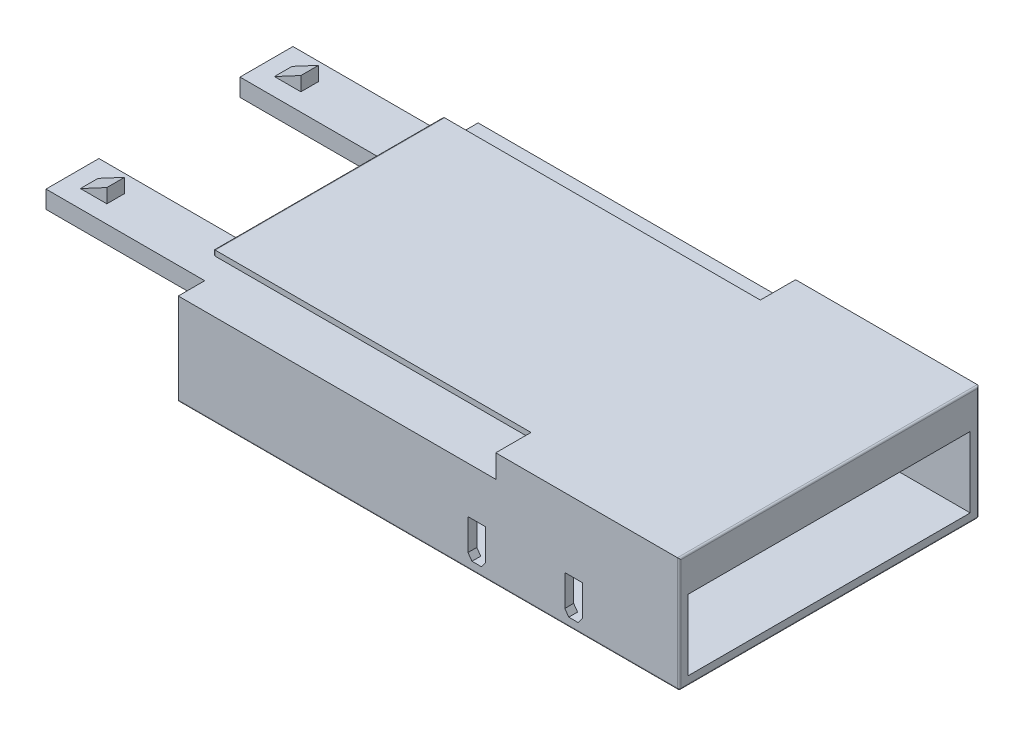
SolidWorks part; units mm, degrees
ref_plane "Front Plane" through (0, 0, 0) normal (0, 0, 1) x (1, 0, 0)
ref_plane "Top Plane" through (0, 0, 0) normal (0, 1, 0) x (1, 0, 0)
ref_plane "Right Plane" through (0, 0, 0) normal (1, 0, 0) x (0, 0, -1)
sketch "Sketch1" plane through (0, 0, 0) normal (0, 1, 0) x (1, 0, 0)
  line L1 (0, 0) -> (284, 0)
  line L2 (0, 0) -> (0, 170)
  line L3 (0, 170) -> (284, 170)
  line L4 (284, 0) -> (284, 170)
  dimension "D1" = 170
  dimension "D2" = 284
extrude "Boss-Extrude1" add sketch "Sketch1" along normal blind 65
sketch "Sketch2" plane through (0, 0, 0) normal (-1, 0, 0) x (0, 0, 1)
  line L0 (-170, 65) -> (-170, 0) construction
  line L1 (-150, 65) -> (-20, 65) construction
  line L2 (-150, 65) -> (-150, 62) construction
  line L3 (-150, 62) -> (-140, 62) construction
  line L4 (-20, 65) -> (-20, 62) construction
  line L6 (-140, 62) -> (-140, 52) construction
  line L7 (-140, 52) -> (-30, 52) construction
  line L8 (-30, 62) -> (-30, 52) construction
  line L9 (-170, 65) -> (0, 65) construction
  line L10 (-30, 62) -> (-20, 62) construction
  line L11 (-140, 52) -> (-170, 52)
  line L12 (-170, 52) -> (-170, 65)
  line L13 (-170, 65) -> (-150, 65)
  line L14 (-150, 65) -> (-150, 62)
  line L15 (-150, 62) -> (-140, 62)
  line L16 (-140, 62) -> (-140, 52)
  line L17 (-30, 52) -> (0, 52)
  line L18 (0, 65) -> (0, 0) construction
  line L19 (0, 52) -> (0, 65)
  line L20 (0, 65) -> (-20, 65)
  line L21 (-20, 65) -> (-20, 62)
  line L22 (-20, 62) -> (-30, 62)
  line L23 (-30, 62) -> (-30, 52)
  dimension "D1" = 130
  dimension "D2" = 3
  dimension "D3" = 10
  dimension "D4" = 110
  dimension "D5" = 20
  dimension "D6" = 10
extrude "Cut-Extrude1" cut sketch "Sketch2" against normal blind 180
sketch "Sketch3" plane through (0, 0, 0) normal (-1, 0, 0) x (0, 0, 1)
  line L0 (-170, 52) -> (-170, 0) construction
  line L1 (-155, 52) -> (-125, 52)
  line L2 (-155, 52) -> (-155, 42)
  line L3 (-155, 42) -> (-125, 42)
  line L4 (-125, 52) -> (-125, 42)
  line L5 (-15, 52) -> (-45, 52)
  line L6 (-15, 52) -> (-15, 42)
  line L7 (-15, 42) -> (-45, 42)
  line L8 (-45, 52) -> (-45, 42)
  line L9 (-170, 52) -> (-140, 52) construction
  line L10 (-30, 52) -> (0, 52) construction
  dimension "D1" = 30
  dimension "D2" = 30
  dimension "D3" = 10
  dimension "D4" = 10
  dimension "D5" = 80
  dimension "D6" = 15
extrude "Boss-Extrude2" add sketch "Sketch3" along normal blind 90
sketch "Sketch4" plane through (0, 52, 0) normal (0, 1, 0) x (1, 0, 0)
  line L0 (0, 125) -> (0, 155) construction
  line L1 (0, 155) -> (-90, 155) construction
  line L2 (0, 30) -> (0, 0) construction
  line L4 (-65.5, 145) -> (-80.5, 145)
  line L5 (-65.5, 145) -> (-65.5, 135)
  line L6 (-65.5, 135) -> (-80.5, 135)
  line L7 (-80.5, 145) -> (-80.5, 135)
  line L8 (0, 15) -> (-90, 15) construction
  line L9 (-65.5, 35) -> (-80.5, 35)
  line L10 (-65.5, 35) -> (-65.5, 25)
  line L11 (-65.5, 25) -> (-80.5, 25)
  line L12 (-80.5, 35) -> (-80.5, 25)
  dimension "D1" = 10
  dimension "D2" = 15
  dimension "D3" = 10
  dimension "D4" = 65.5
  dimension "D5" = 10
  dimension "D6" = 15
  dimension "D7" = 65.5
  dimension "D8" = 10
extrude "Boss-Extrude3" add sketch "Sketch4" along normal blind 8
sketch "Sketch5" plane through (0, 0, -25) normal (0, 0, 1) x (1, 0, 0)
  line L0 (-65.5, 60) -> (-80.5, 52)
  line L1 (-65.5, 60) -> (-80.5, 60)
  line L2 (-80.5, 60) -> (-80.5, 52)
sketch "Sketch6" plane through (0, 0, -145) normal (0, 0, -1) x (-1, 0, 0)
  line L0 (65.5, 60) -> (80.5, 52)
  line L1 (65.5, 60) -> (80.5, 60)
  line L2 (80.5, 60) -> (80.5, 52)
extrude "Cut-Extrude2" cut sketch "Sketch6" against normal blind 10
extrude "Cut-Extrude3" cut sketch "Sketch5" against normal blind 10
sketch "Sketch7" plane through (0, 0, 0) normal (0, -1, 0) x (1, 0, 0)
  line L0 (0, -170) -> (0, 0) construction
  line L3 (11, -37.5) -> (11, -132.5) construction
  line L4 (13.5, -37.5) -> (13.5, -132.5)
  line L5 (8.5, -37.5) -> (8.5, -132.5)
  line L6 (56, -37.5) -> (56, -132.5) construction
  line L7 (58.5, -37.5) -> (58.5, -132.5)
  line L8 (53.5, -37.5) -> (53.5, -132.5)
  line L9 (26, -37.5) -> (26, -132.5) construction
  line L10 (28.5, -37.5) -> (28.5, -132.5)
  line L11 (23.5, -37.5) -> (23.5, -132.5)
  line L12 (41, -37.5) -> (41, -132.5) construction
  line L13 (43.5, -37.5) -> (43.5, -132.5)
  line L14 (38.5, -37.5) -> (38.5, -132.5)
  line L15 (0, -85) -> (284, -85) construction
  line L16 (284, 0) -> (284, -170) construction
  arc A2 (13.5, -37.5) -> (8.5, -37.5) centre (11, -37.5) ccw
  arc A3 (8.5, -132.5) -> (13.5, -132.5) centre (11, -132.5) ccw
  arc A4 (58.5, -37.5) -> (53.5, -37.5) centre (56, -37.5) ccw
  arc A5 (53.5, -132.5) -> (58.5, -132.5) centre (56, -132.5) ccw
  arc A6 (28.5, -37.5) -> (23.5, -37.5) centre (26, -37.5) ccw
  arc A7 (23.5, -132.5) -> (28.5, -132.5) centre (26, -132.5) ccw
  arc A8 (43.5, -37.5) -> (38.5, -37.5) centre (41, -37.5) ccw
  arc A9 (38.5, -132.5) -> (43.5, -132.5) centre (41, -132.5) ccw
  point P9 (11, -85)
  point P16 (56, -85)
  point P23 (26, -85)
  point P30 (41, -85)
  point P35 (11, -35)
  point P36 (11, -135)
  point P42 (26, -35)
  point P43 (26, -135)
  point P44 (41, -35)
  point P45 (41, -135)
  point P46 (56, -35)
  point P47 (56, -135)
  dimension "D1" = 8.5
  dimension "D6" = 100
  dimension "D7" = 100
  dimension "D9" = 100
  dimension "D2" = 5
  dimension "D3" = 5
  dimension "D4" = 5
  dimension "D5" = 5
  dimension "D8" = 100
  dimension "D10" = 15
  dimension "D11" = 15
  dimension "D12" = 15
extrude "Cut-Extrude4" cut sketch "Sketch7" against normal blind 5
sketch "Sketch8" plane through (284, 0, 0) normal (1, 0, 0) x (0, 0, -1)
  line L0 (0, 65) -> (0, 0) construction
  line L1 (5, 45) -> (165, 45)
  line L2 (5, 45) -> (5, 5)
  line L3 (5, 5) -> (165, 5)
  line L4 (165, 45) -> (165, 5)
  line L5 (170, 65) -> (170, 0) construction
  line L6 (0, 0) -> (170, 0) construction
  line L7 (0, 65) -> (170, 65) construction
  dimension "D1" = 5
  dimension "D2" = 5
  dimension "D3" = 5
  dimension "D4" = 20
extrude "Cut-Extrude5" cut sketch "Sketch8" against normal blind 279
sketch "Sketch9" plane through (0, 0, 0) normal (0, 0, 1) x (1, 0, 0)
  line L0 (219.15, 25.8) -> (229.05, 25.8)
  line L1 (164.25, 25.8) -> (174.15, 25.8)
  line L2 (164.25, 25.8) -> (164.25, 8.15)
  line L3 (166.5, 5) -> (171.9, 5)
  line L4 (174.15, 25.8) -> (174.15, 8.15)
  line L5 (219.15, 25.8) -> (219.15, 8.15)
  line L6 (221.4, 5) -> (226.8, 5)
  line L7 (229.05, 25.8) -> (229.05, 8.15)
  line L8 (284, 65) -> (284, 0) construction
  line L9 (0, 0) -> (284, 0) construction
  line L10 (164.25, 8.15) -> (166.5, 5)
  line L11 (171.9, 5) -> (174.15, 8.15)
  line L12 (219.15, 8.15) -> (221.4, 5)
  line L13 (229.05, 8.15) -> (226.8, 5)
  dimension "D1" = 9.9
  dimension "D2" = 3.15
  dimension "D3" = 54.95
  dimension "D4" = 45
  dimension "D5" = 9.9
  dimension "D6" = 20.8
  dimension "D7" = 5
  dimension "D8" = 2.25
  dimension "D9" = 20.8
  dimension "D10" = 2.25
  dimension "D11" = 3.15
  dimension "D12" = 3.15
  dimension "D13" = 3.15
  dimension "D14" = 2.25
  dimension "D15" = 2.25
  dimension "D16" = 25.8
extrude "Cut-Extrude6" cut sketch "Sketch9" against normal blind 5
sketch "Sketch10" plane through (0, 0, 0) normal (-1, 0, 0) x (0, 0, 1)
  line L0 (-170, 20) -> (0, 20) construction
  line L1 (-170, 52) -> (-170, 0) construction
  line L2 (0, 52) -> (0, 0) construction
  line L3 (-170, 0) -> (0, 0) construction
  circle A0 centre (-129.2022, 20) radius 5
  circle A1 centre (-114.2022, 20) radius 5
  circle A2 centre (-99.2022, 20) radius 5
  circle A3 centre (-43.3901, 20) radius 5
  circle A4 centre (-58.3901, 20) radius 5
  circle A5 centre (-73.3901, 20) radius 5
  dimension "D1" = 15
  dimension "D3" = 10
  dimension "D4" = 10
  dimension "D5" = 10
  dimension "D6" = 10
  dimension "D7" = 10
  dimension "D8" = 10
  dimension "D2" = 15
  dimension "D9" = 15
  dimension "D10" = 15
  dimension "D11" = 20
extrude "Cut-Extrude7" cut sketch "Sketch10" against normal blind 5
fillet "Fillet1" radius 1 5 edges at (0, 62, -145) (0, 63.5, -150) (0, 62, -25) (0, 63.5, -20) (0, 65, -85)
fillet "Fillet2" radius 1 7 edges at (284, 32.5, 0) (284, 65, -85) (284, 32.5, -170) (284, 0, -85) (142, 0, 0) (142, 0, -170) (0, 0, -85)
